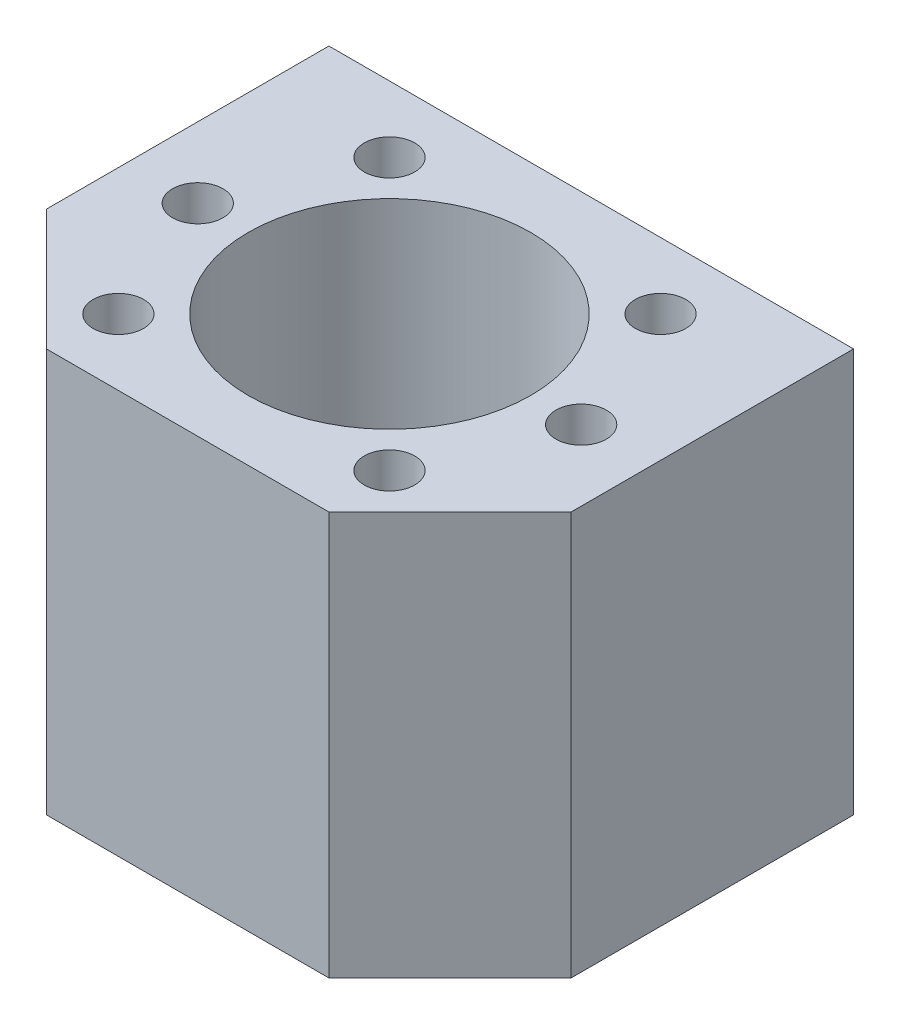
SolidWorks part; units mm, degrees
ref_plane "前视基准面" through (0, 0, 0) normal (0, 0, 1) x (1, 0, 0)
ref_plane "上视基准面" through (0, 0, 0) normal (0, 1, 0) x (1, 0, 0)
ref_plane "右视基准面" through (0, 0, 0) normal (1, 0, 0) x (0, 0, -1)
sketch "草图1" plane through (0, 0, 0) normal (0, 1, 0) x (1, 0, 0)
  line L0 (-26, -8) -> (-14, -20)
  line L1 (-26, 20) -> (26, 20)
  line L2 (-26, 20) -> (-26, -8)
  line L3 (-14, -20) -> (14, -20)
  line L4 (26, 20) -> (26, -8)
  line L5 (-26, 20) -> (26, -20) construction
  line L6 (-26, -20) -> (26, 20) construction
  line L7 (14, -20) -> (26, -8)
  circle A0 centre (0, 0) radius 14
  circle A4 centre (13.435, 13.435) radius 2.5
  circle A5 centre (19, 0) radius 2.5
  circle A6 centre (13.435, -13.435) radius 2.5
  circle A8 centre (-13.435, -13.435) radius 2.5
  circle A9 centre (-19, 0) radius 2.5
  circle A10 centre (-13.435, 13.435) radius 2.5
  point P0 (0, 0)
  point P33 (0, 0)
  dimension "D3" = 28
  dimension "D1" = 52
  dimension "D2" = 40
extrude "凸台-拉伸1" add sketch "草图1" along normal blind 40
sketch "草图2" plane through (0, 0, -20) normal (0, 0, -1) x (-1, 0, 0)
  line L1 (-26, 0) -> (26, 0) construction
  circle A0 centre (-20, 32) radius 2.5
  circle A1 centre (-20, 8) radius 2.5
  circle A2 centre (20, 32) radius 2.5
  circle A3 centre (20, 8) radius 2.5
  point P8 (0, 0)
  dimension "D3" = 5
  dimension "D4" = 5
  dimension "D5" = 5
  dimension "D6" = 5
  dimension "D1" = 40
  dimension "D2" = 20
  dimension "D7" = 24
  dimension "D8" = 8
extrude "切除-拉伸1" cut sketch "草图2" against normal blind 10
